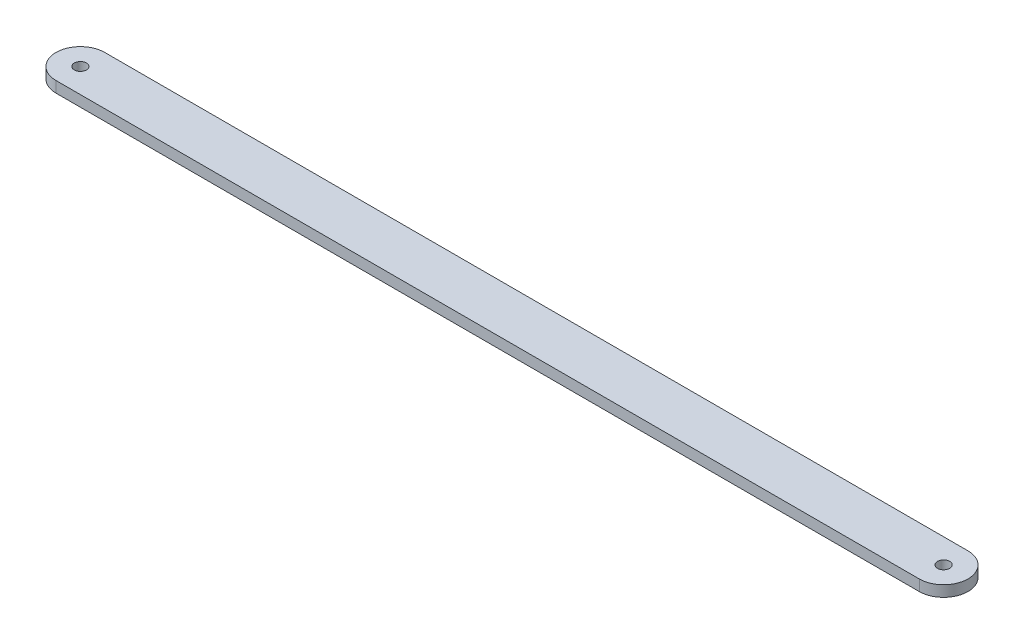
SolidWorks part; units mm, degrees
ref_plane "前基準面" through (0, 0, 0) normal (0, 0, 1) x (1, 0, 0)
ref_plane "上基準面" through (0, 0, 0) normal (0, 1, 0) x (1, 0, 0)
ref_plane "右基準面" through (0, 0, 0) normal (1, 0, 0) x (0, 0, -1)
sketch "草圖1" plane through (0, 0, 0) normal (0, 1, 0) x (1, 0, 0)
  line L0 (-177.245, 0) -> (177.245, 0) construction
  line L1 (-177.245, 10) -> (177.245, 10)
  line L2 (-177.245, -10) -> (177.245, -10)
  arc A0 (-177.245, 10) -> (-177.245, -10) centre (-177.245, 0) ccw
  arc A1 (177.245, -10) -> (177.245, 10) centre (177.245, 0) ccw
  circle A2 centre (-177.245, 0) radius 2.5
  circle A3 centre (177.245, 0) radius 2.5
  point P3 (0, 0)
  dimension "D2" = 10
  dimension "D3" = 5
  dimension "D1" = 354.49
extrude "填料-伸長1" add sketch "草圖1" along normal blind 4.5
